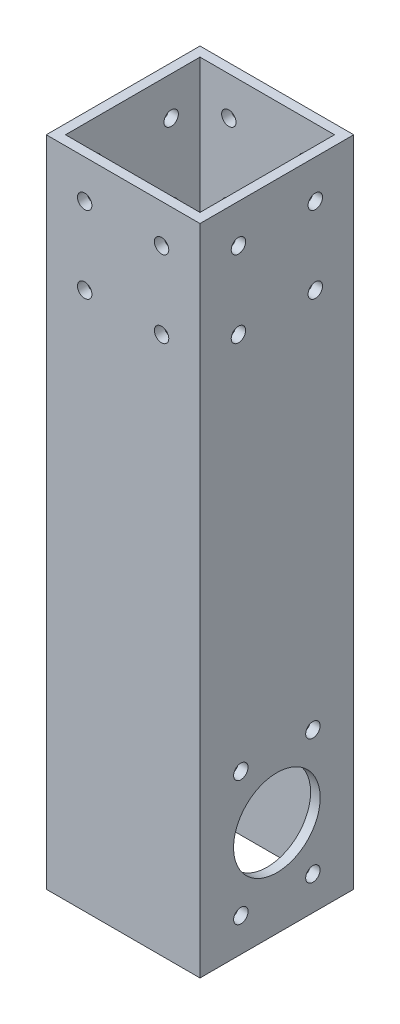
SolidWorks part; units mm, degrees
ref_plane "Front Plane" through (0, 0, 0) normal (0, 0, 1) x (1, 0, 0)
ref_plane "Top Plane" through (0, 0, 0) normal (0, 1, 0) x (1, 0, 0)
ref_plane "Right Plane" through (0, 0, 0) normal (1, 0, 0) x (0, 0, -1)
sketch "Sketch1" plane through (0, 0, 0) normal (0, 1, 0) x (1, 0, 0)
  line L1 (-25.4, 25.4) -> (25.4, 25.4)
  line L2 (-25.4, 25.4) -> (-25.4, -25.4)
  line L3 (-25.4, -25.4) -> (25.4, -25.4)
  line L4 (25.4, 25.4) -> (25.4, -25.4)
  line L5 (-25.4, 25.4) -> (25.4, -25.4) construction
  line L6 (-25.4, -25.4) -> (25.4, 25.4) construction
  point P0 (0, 0)
  dimension "D1" = 50.8
  dimension "D2" = 50.8
extrude "Boss-Extrude1" add sketch "Sketch1" along normal blind 215.9
shell "Shell1" thickness 3.175
sketch "Sketch2" plane through (25.4, 0, 0) normal (1, 0, 0) x (0, 0, -1)
  line L0 (-25.4, 0) -> (25.4, 0) construction
  circle A0 centre (0, 31.75) radius 14.3129
  dimension "D1" = 28.6258
  dimension "D2" = 31.75
extrude "Cut-Extrude1" cut sketch "Sketch2" against normal through all
sketch "Sketch3" plane through (25.4, 0, 0) normal (1, 0, 0) x (0, 0, -1)
  line L0 (0, 0) -> (0, 31.75) construction
  line L1 (-25.4, 0) -> (25.4, 0) construction
  line L2 (0, 31.75) -> (-11.9063, 52.3722) construction
  circle A0 centre (0, 31.75) radius 23.8125 construction
  circle A1 centre (-11.9063, 52.3722) radius 2.3812
  circle A2 centre (11.9062, 52.3722) radius 2.3812
  circle A3 centre (23.8125, 31.75) radius 2.3812
  circle A4 centre (11.9063, 11.1278) radius 2.3812
  circle A5 centre (-11.9062, 11.1278) radius 2.3813
  circle A6 centre (-23.8125, 31.75) radius 2.3812
  point P6 (-22.2009, 31.3902)
  point P9 (11.0697, 39.4086)
  point P10 (0, 0)
  point P21 (0, 31.75)
  dimension "D1" = 47.625
  dimension "D2" = 4.7625
  dimension "D3" = 150
  dimension "D4" = 6
extrude "Cut-Extrude2" cut sketch "Sketch3" against normal through all contours A1 | A2 | A5 | A4
sketch "Sketch4" plane through (25.4, 0, 0) normal (1, 0, 0) x (0, 0, -1)
  line L0 (-25.4, 215.9) -> (25.4, 215.9) construction
  line L1 (-25.4, 215.9) -> (-25.4, 0) construction
  circle A0 centre (-12.7, 203.2) radius 2.3812
  circle A1 centre (12.7, 203.2) radius 2.3812
  circle A2 centre (12.7, 177.8) radius 2.3812
  circle A3 centre (-12.7, 177.8) radius 2.3812
  dimension "D5" = 4.7625
  dimension "D1" = 12.7
  dimension "D2" = 12.7
  dimension "D3" = 2
  dimension "D4" = 2
extrude "Cut-Extrude3" cut sketch "Sketch4" against normal through all
sketch "Sketch5" plane through (0, 0, 25.4) normal (0, 0, 1) x (1, 0, 0)
  line L0 (-25.4, 215.9) -> (25.4, 215.9) construction
  line L1 (-25.4, 215.9) -> (-25.4, 0) construction
  circle A0 centre (-12.7, 203.2) radius 2.3812
  circle A1 centre (12.7, 203.2) radius 2.3812
  circle A2 centre (12.7, 177.8) radius 2.3812
  circle A3 centre (-12.7, 177.8) radius 2.3812
  dimension "D1" = 4.7625
  dimension "D2" = 12.7
  dimension "D3" = 12.7
  dimension "D4" = 2
  dimension "D5" = 2
extrude "Cut-Extrude4" cut sketch "Sketch5" against normal through all
